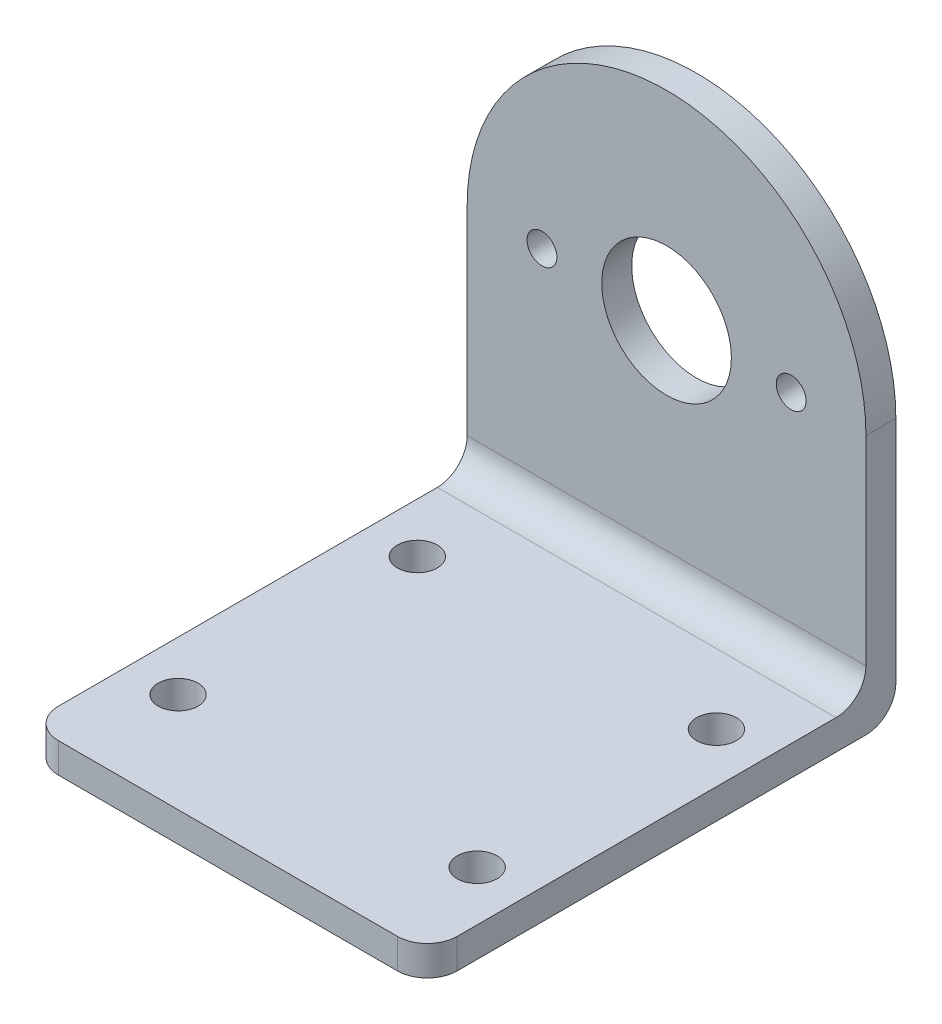
SolidWorks part; units mm, degrees
ref_plane "Спереди" through (0, 0, 0) normal (0, 0, 1) x (1, 0, 0)
ref_plane "Сверху" through (0, 0, 0) normal (0, 1, 0) x (1, 0, 0)
ref_plane "Справа" through (0, 0, 0) normal (1, 0, 0) x (0, 0, -1)
sketch "Эскиз1" plane through (0, 0, 0) normal (0, 0, 1) x (1, 0, 0)
  line L0 (-7.2365, 26) -> (46.7607, 26) construction
  line L1 (0, 0) -> (40, 0)
  line L2 (0, 0) -> (0, 26)
  line L4 (40, 0) -> (40, 26)
  circle A0 centre (20, 26) radius 6.5
  arc A1 (40, 26) -> (0, 26) centre (20, 26) ccw
  circle A2 centre (32.5, 26) radius 1.5
  circle A3 centre (7.5, 26) radius 1.5
extrude "Бобышка-Вытянуть1" add sketch "Эскиз1" along normal blind 3
sketch "Эскиз2" plane through (0, 0, 3) normal (0, 0, 1) x (1, 0, 0)
  line L0 (40, 0) -> (40, 26) construction
  line L1 (0, 0) -> (40, 0)
  line L2 (0, 0) -> (0, 3)
  line L3 (0, 3) -> (40, 3)
  line L4 (40, 0) -> (40, 3)
  dimension "D1" = 3
extrude "Бобышка-Вытянуть2" add sketch "Эскиз2" along normal blind 44
fillet "Скругление4" radius 3 1 edges at (20, 0, 0)
sketch "Эскиз3" plane through (0, 0, 0) normal (0, -1, 0) x (1, 0, 0)
  line L1 (0, 47) -> (40, 47) construction
  line L2 (35, 47) -> (35, 3) construction
  line L3 (0, 3) -> (40, 3) construction
  line L5 (5, 47) -> (5, 3) construction
  circle A0 centre (5, 37) radius 2
  circle A1 centre (35, 37) radius 2
  circle A2 centre (5, 13) radius 2
  circle A3 centre (35, 13) radius 2
  dimension "D1" = 4
  dimension "D2" = 4
  dimension "D3" = 4
  dimension "D4" = 4
extrude "Вырез-Вытянуть1" cut sketch "Эскиз3" against normal through all
fillet "Скругление5" radius 3 1 edges
fillet "Скругление6" radius 3 2 edges at (40, 1.5, 47) (0, 1.5, 47)
